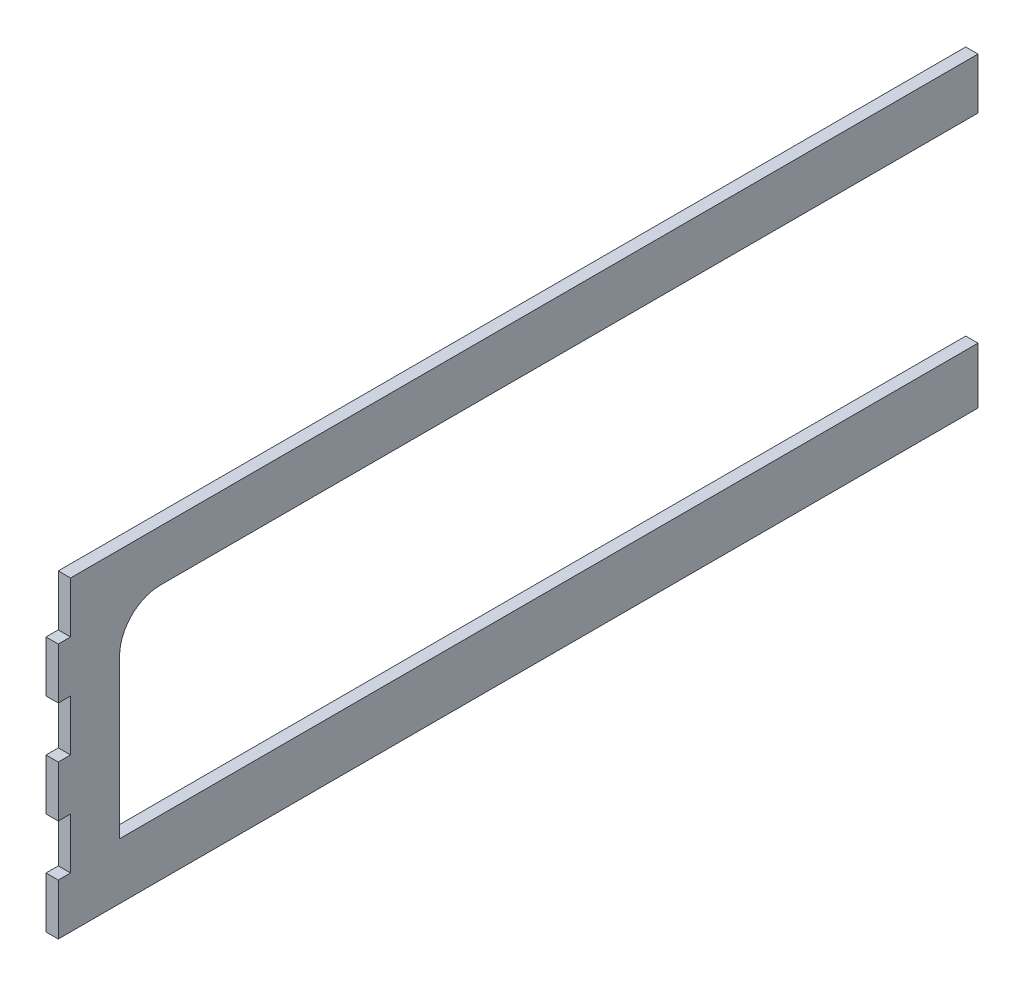
SolidWorks part; units mm, degrees
ref_plane "Front" through (0, 0, 0) normal (0, 0, 1) x (1, 0, 0)
ref_plane "Top" through (0, 0, 0) normal (0, 1, 0) x (1, 0, 0)
ref_plane "Right" through (0, 0, 0) normal (1, 0, 0) x (0, 0, -1)
sketch "Sketch1" plane through (0, 0, 0) normal (1, 0, 0) x (0, 0, -1)
  line L0 (450, 125) -> (450, 150)
  line L1 (0, 0) -> (450, 0)
  line L2 (0, 0) -> (0, 150)
  line L3 (0, 150) -> (450, 150)
  line L4 (450, 0) -> (450, 27.5)
  line L5 (450, 125) -> (30, 125)
  line L7 (450, 27.5) -> (30, 27.5)
  line L8 (30, 125) -> (30, 27.5)
  dimension "D1" = 420
  dimension "D2" = 150
  dimension "D3" = 27.5
  dimension "D4" = 25
  dimension "D5" = 30
extrude "Boss-Extrude1" add sketch "Sketch1" along normal blind 6
sketch "Sketch2" plane through (6, 0, 0) normal (1, 0, 0) x (0, 0, -1)
  line L1 (0, 150) -> (6, 150)
  line L2 (0, 150) -> (0, 125)
  line L3 (0, 125) -> (6, 125)
  line L4 (6, 150) -> (6, 125)
  dimension "D1" = 6
  dimension "D2" = 25
extrude "Cut-Extrude1" cut sketch "Sketch2" against normal blind 6
pattern_linear "LPattern1" count 3 spacing 50 along (0, -1, 0) of "Cut-Extrude1"
fillet "Fillet1" radius 20 1 edges at (3, 125, -30)
